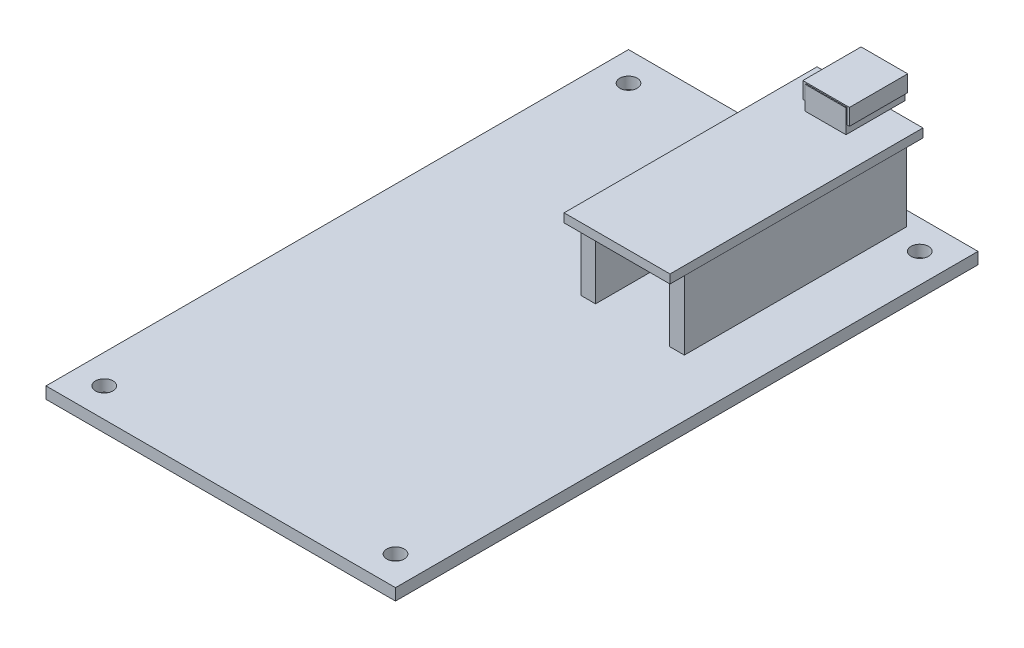
SolidWorks part; units mm, degrees
ref_plane "Alzado" through (0, 0, 0) normal (0, 0, 1) x (1, 0, 0)
ref_plane "Planta" through (0, 0, 0) normal (0, 1, 0) x (1, 0, 0)
ref_plane "Vista lateral" through (0, 0, 0) normal (1, 0, 0) x (0, 0, -1)
sketch "Croquis1" plane through (0, 0, 0) normal (0, 1, 0) x (1, 0, 0)
  line L0 (-30, 0) -> (30, 0) construction
  line L1 (-30, -50) -> (30, -50)
  line L2 (-30, -50) -> (-30, 50)
  line L3 (-30, 50) -> (30, 50)
  line L4 (30, -50) -> (30, 50)
  line L5 (-30, -50) -> (30, 50) construction
  line L6 (-30, 50) -> (30, -50) construction
  line L7 (0, 50) -> (0, 0) construction
  circle A0 centre (-25, 45) radius 1.5
  circle A2 centre (25, 45) radius 1.5
  circle A3 centre (25, -45) radius 1.5
  circle A4 centre (-25, -45) radius 1.5
  point P0 (0, 0)
  dimension "D5" = 3
  dimension "D1" = 60
  dimension "D2" = 100
  dimension "D3" = 5
  dimension "D4" = 5
extrude "Saliente-Extruir1" add sketch "Croquis1" along normal blind 2
sketch "Croquis2" plane through (0, 2, 0) normal (0, 1, 0) x (1, 0, 0)
  line L1 (4.981, 9.365) -> (2.441, 9.365)
  line L2 (4.981, 9.365) -> (4.981, 47.465)
  line L3 (4.981, 47.465) -> (2.441, 47.465)
  line L4 (2.441, 9.365) -> (2.441, 47.465)
  line L5 (4.981, 9.365) -> (2.441, 47.465) construction
  line L6 (4.981, 47.465) -> (2.441, 9.365) construction
  line L7 (30, -50) -> (30, 50) construction
  line L8 (20.221, 9.365) -> (17.681, 9.365)
  line L9 (20.221, 9.365) -> (20.221, 47.465)
  line L10 (20.221, 47.465) -> (17.681, 47.465)
  line L11 (17.681, 9.365) -> (17.681, 47.465)
  line L12 (20.221, 9.365) -> (17.681, 47.465) construction
  line L13 (20.221, 47.465) -> (17.681, 9.365) construction
  line L14 (30, 50) -> (-30, 50) construction
  point P0 (3.711, 28.415)
  point P7 (18.951, 28.415)
  dimension "D1" = 15.24
  dimension "D2" = 11.049
  dimension "D3" = 2.54
  dimension "D4" = 2.54
  dimension "D5" = 38.1
  dimension "D6" = 38.1
  dimension "D7" = 2.535
extrude "Saliente-Extruir2" add sketch "Croquis2" along normal blind 12
sketch "Croquis3" plane through (0, 14, 0) normal (0, 1, 0) x (1, 0, 0)
  line L0 (2.441, 28.415) -> (20.221, 28.415) construction
  line L1 (20.221, 47.465) -> (2.441, 47.465)
  line L2 (20.221, 47.465) -> (20.221, 9.365)
  line L3 (20.221, 9.365) -> (2.441, 9.365)
  line L4 (2.441, 47.465) -> (2.441, 9.365)
  line L5 (11.331, 47.465) -> (11.331, 9.365) construction
  line L7 (20.421, 6.705) -> (2.241, 6.705)
  line L8 (20.421, 6.705) -> (20.421, 50.125)
  line L9 (20.421, 50.125) -> (2.241, 50.125)
  line L10 (2.241, 6.705) -> (2.241, 50.125)
  line L11 (20.421, 6.705) -> (2.241, 50.125) construction
  line L12 (20.421, 50.125) -> (2.241, 6.705) construction
  point P10 (11.331, 28.415)
  dimension "D1" = 0.2
  dimension "D2" = 2.66
extrude "Saliente-Extruir3" add sketch "Croquis3" along normal blind 1.5 separate body contours L8 L9 L10 L7
sketch "Croquis4" plane through (0, 15.5, 0) normal (0, 1, 0) x (1, 0, 0)
  line L0 (11.331, 47.585) -> (11.331, 50.125) construction
  line L1 (14.831, 42.505) -> (7.831, 42.505)
  line L2 (14.831, 42.505) -> (14.831, 52.665)
  line L3 (14.831, 52.665) -> (7.831, 52.665)
  line L4 (7.831, 42.505) -> (7.831, 52.665)
  line L5 (14.831, 42.505) -> (7.831, 52.665) construction
  line L6 (14.831, 52.665) -> (7.831, 42.505) construction
  line L7 (20.421, 50.125) -> (2.241, 50.125) construction
  point P0 (11.331, 47.585)
  point P9 (11.331, 50.125)
  dimension "D1" = 7
  dimension "D2" = 10.16
  dimension "D3" = 7.62
extrude "Saliente-Extruir4" add sketch "Croquis4" along normal blind 4
sketch "Croquis5" plane through (0, 0, -52.665) normal (0, 0, -1) x (-1, 0, 0)
  line L0 (-15.2649, 16.89) -> (-14.7649, 16.89)
  line L1 (-14.7649, 16.89) -> (-14.7649, 15.5)
  line L2 (-14.7649, 15.5) -> (-7.7649, 15.5)
  line L3 (-7.7649, 15.5) -> (-7.7649, 16.89)
  line L4 (-7.7649, 16.89) -> (-7.2649, 16.89)
  line L5 (-7.2649, 16.89) -> (-7.2649, 19.7)
  line L6 (-7.2649, 19.7) -> (-15.2649, 19.7)
  line L7 (-15.2649, 19.7) -> (-15.2649, 16.89)
  line L8 (-7.831, 15.5) -> (-2.241, 15.5) construction
  dimension "D1" = 0.5
  dimension "D2" = 7
  dimension "D3" = 1.39
  dimension "D5" = 0.5
  dimension "D7" = 2.81
  dimension "D8" = 2.81
extrude "Saliente-Extruir5" add sketch "Croquis5" against normal blind 10
